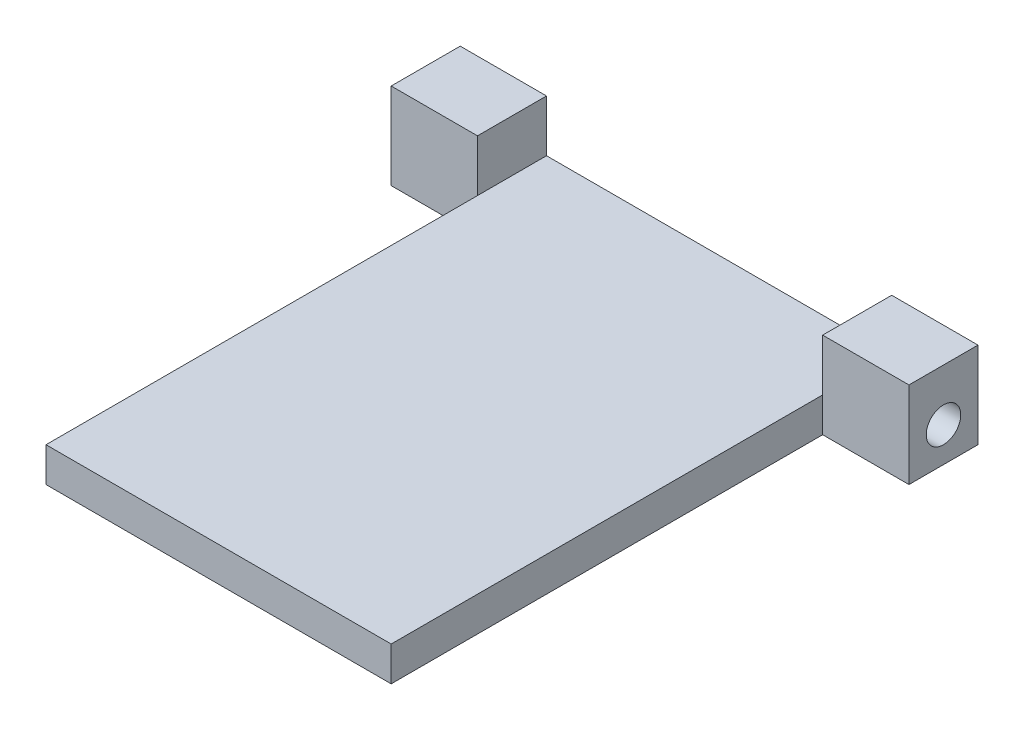
SolidWorks part; units mm, degrees
ref_plane "Front Plane" through (0, 0, 0) normal (0, 0, 1) x (1, 0, 0)
ref_plane "Top Plane" through (0, 0, 0) normal (0, 1, 0) x (1, 0, 0)
ref_plane "Right Plane" through (0, 0, 0) normal (1, 0, 0) x (0, 0, -1)
ref_plane "Plane2" through (0, -50, 0) normal (0, -1, 0) x (-1, 0, 0)
sketch "Sketch5" plane through (0, -50, 0) normal (0, -1, 0) x (-1, 0, 0)
  line L0 (50, 85) -> (-50, 85)
  line L1 (-50, 85) -> (-50, -85)
  line L2 (-50, -85) -> (50, -85)
  line L3 (50, -85) -> (50, 85)
extrude "Boss-Extrude2" add sketch "Sketch5" against normal blind 10 separate body
sketch "Sketch7" plane through (-50, 0, 0) normal (-1, 0, 0) x (0, 0, 1)
  line L0 (-85, -50) -> (-65, -50)
  line L1 (85, -50) -> (-85, -50) construction
  line L2 (-65, -50) -> (-65, -25)
  line L3 (-65, -25) -> (-85, -25)
  line L4 (-85, -25) -> (-85, -50)
  dimension "D1" = 20
  dimension "D2" = 25
extrude "Boss-Extrude3" add sketch "Sketch7" along normal blind 25
sketch "Sketch8" plane through (50, 0, 0) normal (1, 0, 0) x (0, 0, -1)
  line L0 (65, -50) -> (65, -25)
  line L1 (65, -25) -> (85, -25)
  line L2 (85, -25) -> (85, -50)
  line L3 (85, -50) -> (65, -50)
extrude "Boss-Extrude4" add sketch "Sketch8" along normal blind 25
sketch "Sketch11" plane through (-75, 0, 0) normal (-1, 0, 0) x (0, 0, 1)
  line L0 (-85, -25) -> (-85, -50) construction
  line L1 (-85, -50) -> (-65, -50) construction
  circle A0 centre (-75, -40) radius 5
  dimension "D3" = 10
  dimension "D1" = 10
  dimension "D2" = 10
extrude "Cut-Extrude1" cut sketch "Sketch11" against normal blind 20
sketch "Sketch12" plane through (75, 0, 0) normal (1, 0, 0) x (0, 0, -1)
  line L0 (65, -50) -> (85, -50) construction
  line L1 (85, -50) -> (85, -25) construction
  circle A0 centre (75, -40) radius 5
  dimension "D1" = 10
  dimension "D2" = 10
  dimension "D3" = 10
extrude "Cut-Extrude2" cut sketch "Sketch12" against normal blind 20
sketch "Sketch17" plane through (0, 0, 85) normal (0, 0, 1) x (1, 0, 0)
  line L0 (-50, -50) -> (-50, -40)
  line L1 (-50, -40) -> (50, -40)
  line L2 (50, -40) -> (50, -50)
  line L3 (50, -50) -> (-50, -50)
extrude "Boss-Extrude6" add sketch "Sketch17" along normal blind 100
sketch "Sketch18" plane through (0, -40, 0) normal (0, 1, 0) x (1, 0, 0)
  line L0 (-50, -60) -> (50, -60)
  line L1 (-50, -185) -> (-50, 65) construction
  line L2 (50, 65) -> (50, -185) construction
  line L3 (50, -60) -> (50, -185)
  line L4 (50, -185) -> (-50, -185)
  line L5 (-50, -185) -> (-50, -60)
  dimension "D1" = 100
  dimension "D2" = 125
extrude "Cut-Extrude3" cut sketch "Sketch18" against normal blind 10
